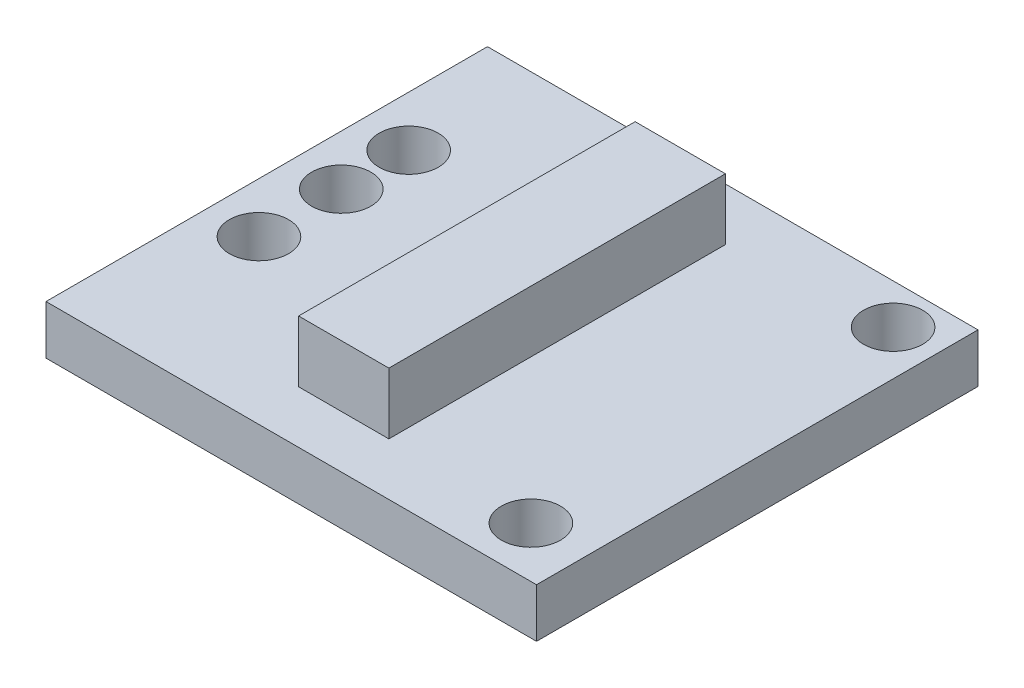
SolidWorks part; units mm, degrees
ref_plane "Front Plane" through (0, 0, 0) normal (0, 0, 1) x (1, 0, 0)
ref_plane "Top Plane" through (0, 0, 0) normal (0, 1, 0) x (1, 0, 0)
ref_plane "Right Plane" through (0, 0, 0) normal (1, 0, 0) x (0, 0, -1)
sketch "Sketch1" plane through (0, 0, 0) normal (0, 1, 0) x (1, 0, 0)
  line L1 (5, -4.5) -> (-5, -4.5)
  line L2 (5, -4.5) -> (5, 4.5)
  line L3 (5, 4.5) -> (-5, 4.5)
  line L4 (-5, -4.5) -> (-5, 4.5)
  line L5 (5, -4.5) -> (-5, 4.5) construction
  line L6 (5, 4.5) -> (-5, -4.5) construction
  circle A0 centre (-3.9745, -1.184) radius 0.6031
  circle A1 centre (-3.9745, 0.4935) radius 0.6031
  circle A2 centre (-3.9745, 1.8684) radius 0.6031
  circle A3 centre (4.0891, 3.6801) radius 0.6031
  circle A4 centre (3.8553, -3.4698) radius 0.6031
  point P0 (0, 0)
  point P16 (3.8553, -3.4698)
  dimension "D1" = 9
  dimension "D2" = 10
extrude "Boss-Extrude1" add sketch "Sketch1" along normal blind 1
sketch "Sketch2" plane through (0, 1, 0) normal (0, 1, 0) x (1, 0, 0)
  line L1 (0.9202, -3.4306) -> (-0.9202, -3.4306)
  line L2 (0.9202, -3.4306) -> (0.9202, 3.4306)
  line L3 (0.9202, 3.4306) -> (-0.9202, 3.4306)
  line L4 (-0.9202, -3.4306) -> (-0.9202, 3.4306)
  line L5 (0.9202, -3.4306) -> (-0.9202, 3.4306) construction
  line L6 (0.9202, 3.4306) -> (-0.9202, -3.4306) construction
  point P0 (0, 0)
extrude "Boss-Extrude2" add sketch "Sketch2" along normal blind 1.25
